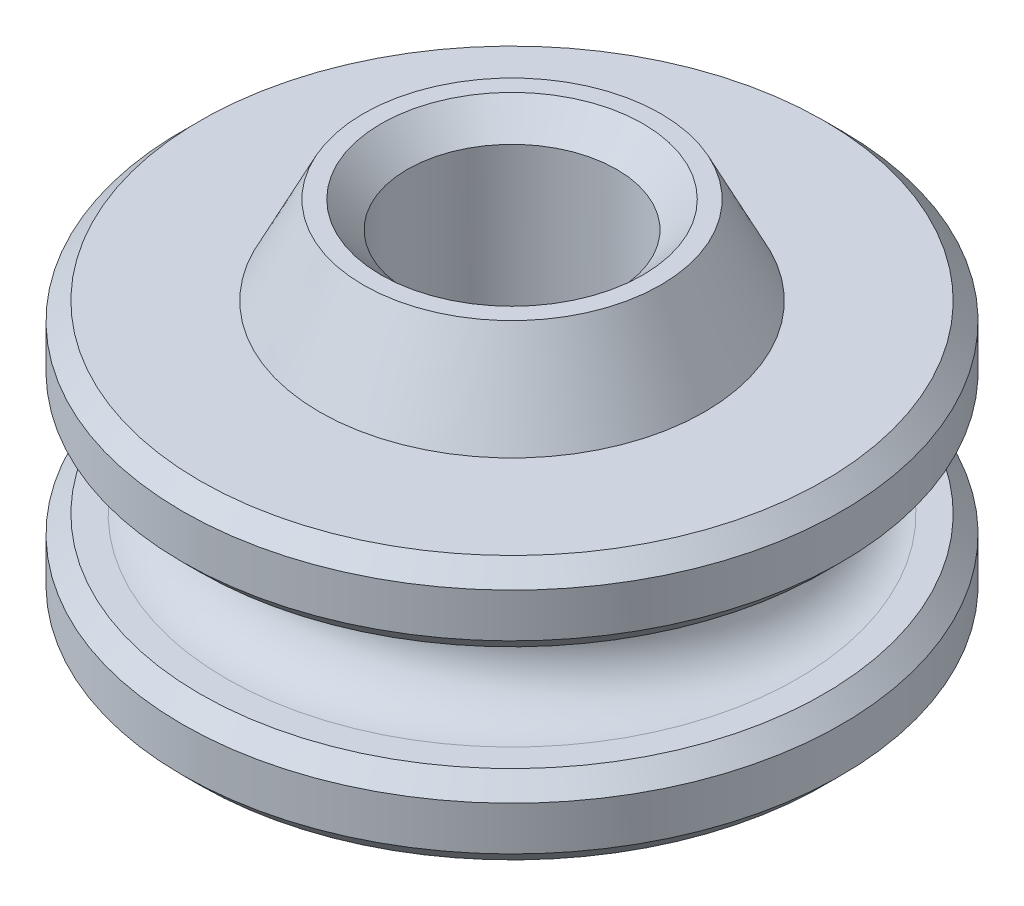
SolidWorks part; units mm, degrees
ref_plane "Front Plane" through (0, 0, 0) normal (0, 0, 1) x (1, 0, 0)
ref_plane "Top Plane" through (0, 0, 0) normal (0, 1, 0) x (1, 0, 0)
ref_plane "Right Plane" through (0, 0, 0) normal (1, 0, 0) x (0, 0, -1)
ref_axis "Axis1" through (0, 2.7, 0) along (0, -1, 0)
sketch "Sketch1" plane through (0, 0, 0) normal (1, 0, 0) x (0, 0, -1)
  line L0 (55, 0) -> (-55, 0) construction
  line L4 (1.191, 2.5) -> (1.191, -1.5)
  line L9 (0, 55) -> (0, -55) construction
  line L10 (1.191, -1.5) -> (2.191, -1.5)
  line L12 (1.191, 2.5) -> (1.691, 2.5)
  line L13 (1.691, 2.5) -> (2.191, 1.5)
  line L14 (2.191, 1.5) -> (3.75, 1.5)
  line L15 (2.191, -1.5) -> (3.75, -1.5)
  line L16 (3.25, 0.6) -> (3.75, 0.6)
  line L17 (3.25, -0.6) -> (3.75, -0.6)
  line L18 (3.75, -0.6) -> (3.75, -1.5)
  line L19 (3.75, 0.6) -> (3.75, 1.5)
  circle A0 centre (3.25, 0) radius 0.6 construction
  arc A1 (3.25, 0.6) -> (3.25, -0.6) centre (3.25, 0) ccw
  point P9 (2.191, 1.5)
  point P16 (2.191, -1.5)
  dimension "D2" = 1.2
  dimension "D1" = 3.25
  dimension "D3" = 1.191
  dimension "D4" = 0.5
  dimension "D5" = 3
  dimension "D7" = 3.75
  dimension "D6" = 2.5
  dimension "D8" = 0.5
revolve "Revolve1" add sketch "Sketch1" angle 360 about axis through (0, 2.7, 0) along (0, -1, 0)
chamfer "Chamfer1" distance 0.3 angle 45 2 edges at (0, 2.5, 1.191) (0, -1.5, 1.191)
chamfer "Chamfer2" distance 0.2 angle 45 4 edges at (0, 1.5, 3.75) (0, 0.6, 3.75) (0, -0.6, 3.75) (0, -1.5, 3.75)
equation "\"d_pulley\"= 6.5"
equation "\"D1@Sketch1\"=\"d_pulley\"/2"
equation "\"d_rope\"=1.2"
equation "\"D2@Sketch1\"=\"d_rope\""
equation "\"d_shaft\"= 2.382"
equation "\"D3@Sketch1\"=\"d_shaft\"/2"
equation "\"w_pulley\"=3"
equation "\"D5@Sketch1\"=\"w_pulley\""
equation "\"d_outside\"= 7.5"
equation "\"D7@Sketch1\"=\"d_outside\"/2"
equation "\"plane_offset\"=2.5"
equation "\"D6@Sketch1\"=\"plane_offset\""
